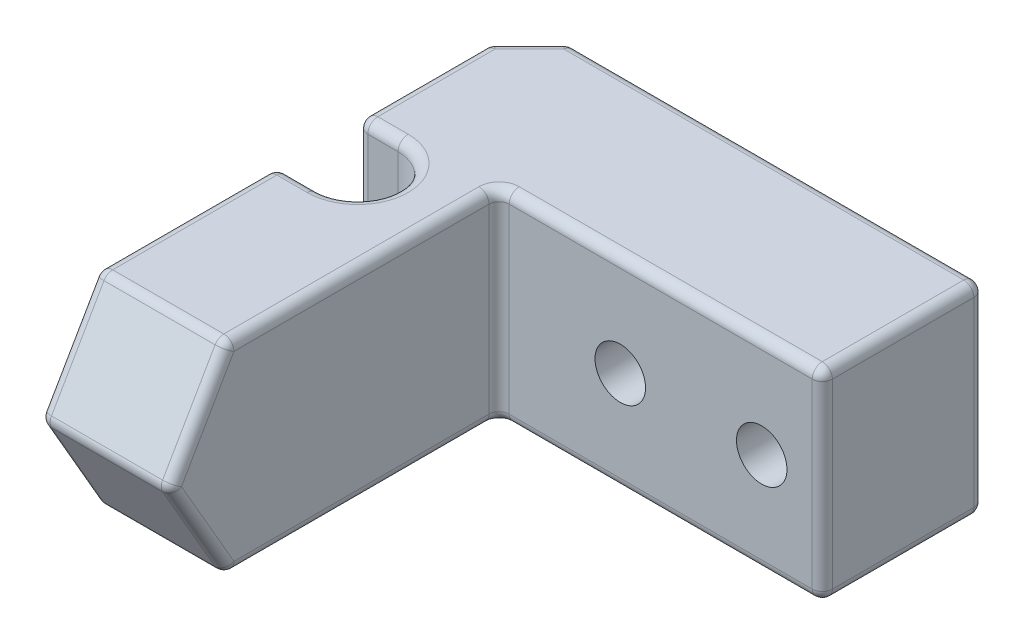
SolidWorks part; units mm, degrees
material "Acier allié"
ref_plane "Plan de face" through (0, 0, 0) normal (0, 0, 1) x (1, 0, 0)
ref_plane "Plan de dessus" through (0, 0, 0) normal (0, 1, 0) x (1, 0, 0)
ref_plane "Plan de droite" through (0, 0, 0) normal (1, 0, 0) x (0, 0, -1)
sketch "Esquisse1" plane through (0, 0, 0) normal (0, 0, 1) x (1, 0, 0)
  line L1 (0, 0) -> (22.5, 0)
  line L2 (0, 0) -> (0, 10)
  line L3 (0, 10) -> (22.5, 10)
  line L4 (22.5, 0) -> (22.5, 10)
  dimension "D1" = 10
  dimension "D2" = 22.5
extrude "Boss.-Extru.1" add sketch "Esquisse1" along normal blind 8
chamfer "Chanfrein1" distance 2 angle 45 1 edges at (0, 5, 0)
sketch "Esquisse3" plane through (0, 0, 0) normal (-1, 0, 0) x (0, 0, 1)
  line L0 (8, 10) -> (21.4132, 10)
  line L1 (21.4132, 10) -> (24.3, 5)
  line L2 (24.3, 5) -> (21.4132, 0)
  line L3 (21.4132, 0) -> (8, 0)
  line L4 (8, 5) -> (24.3, 5) construction
  line L5 (8, 10) -> (8, 0) construction
  line L10 (8, 10) -> (2, 10)
  line L11 (2, 10) -> (2, 0)
  line L12 (2, 0) -> (8, 0)
  line L13 (8, 0) -> (8, 10)
  line L14 (8, 10) -> (2, 10)
  line L15 (2, 10) -> (2, 0)
  line L16 (2, 0) -> (8, 0)
  dimension "D1" = 16.3
  dimension "D2" = 60
  dimension "D3" = 0
extrude "Boss.-Extru.3" add sketch "Esquisse3" against normal blind 6.5
sketch "Esquisse4" plane through (0, 10, 0) normal (0, 1, 0) x (1, 0, 0)
  line L0 (0, 0) -> (0, -8.5) construction
  line L1 (0, -8.5) -> (2, -8.5)
  line L2 (0, -8.5) -> (0, -12.5)
  line L3 (0, -12.5) -> (2, -12.5)
  line L4 (2, -8.5) -> (2, -12.5) construction
  arc A0 (2, -12.5) -> (2, -8.5) centre (2, -10.5) ccw
  dimension "D1" = 8.5
  dimension "D2" = 4
  dimension "D3" = 2
extrude "Enlèv. mat.-Extru.1" cut sketch "Esquisse4" against normal blind 7
hole_wizard "Trou taraudé M33" positions "Esquisse3D1" profile "Esquisse7" tap size "M3" standard "ISO" end condition through all
sketch3d "Esquisse3D1"
  line L0 (22.5, 5, 0) -> (2, 5, 0) construction
  line L1 (22.5, 0, 0) -> (22.5, 10, 0) construction
  line L2 (2, 0, 0) -> (2, 10, 0) construction
  point P0 (19.5, 5, 0)
  point P2 (12.5, 5, 0)
  point P9 (0, 0, 0)
  point P10 (0, 0, 0)
  dimension "D1" = 3
  dimension "D2" = 7
sketch "Esquisse7" plane through (19.5, 5, 0) normal (1, 0, 0) x (0, 1, 0)
  line L0 (0, 0) -> (0, 24.3)
  line L1 (0, 24.3) -> (1.25, 24.3)
  line L2 (1.25, 24.3) -> (1.25, 0)
  line L5 (1.25, 0) -> (0, 0)
  line L11 (0, -6.35) -> (0, 107.95) construction
  dimension "Diamètre du trou pour taraudage jusqu'au prochain" = 2.5
  dimension "Profondeur du trou pour taraudage jusqu'au prochain" = 24.3
cosmetic thread "Filetage de perçage1" parameters "D2"=3
cosmetic thread "Filetage de perçage2" parameters "D2"=3
fillet "Congé1" radius 0.5 34 edges at (0, 10, 5.25) (3.25, 5, 24.3) (3.25, 0, 21.4132) (14.5, 0, 8) (12.25, 0, 0) (1, 0, 1) (2, 5, 0) (1, 3, 8.5) (4, 3, 10.5) (1, 3, 12.5) (22.5, 0, 4) (22.5, 5, 8) (22.5, 5, 0) (6.5, 2.5, 22.8566) (6.5, 7.5, 22.8566) (6.5, 5, 8) (6.5, 0, 14.7066) (1, 10, 1) (12.25, 10, 0) (22.5, 10, 4) (14.5, 10, 8) (6.5, 10, 14.7066) (3.25, 10, 21.4132) (1, 10, 12.5) (4, 10, 10.5) (1, 10, 8.5) (0, 6.5, 12.5) (0, 10, 16.9566) (0, 7.5, 22.8566) (0, 2.5, 22.8566) (0, 0, 11.7066) (0, 5, 2) (0, 6.5, 8.5) (0, 3, 10.5)
